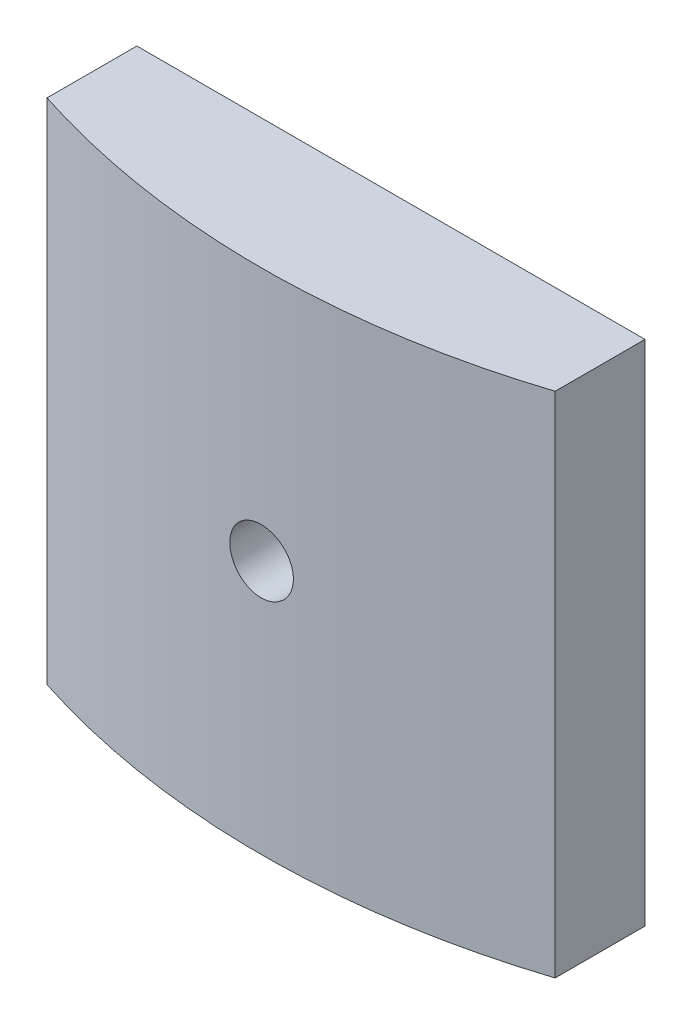
SolidWorks part; units mm, degrees
material "ABS"
ref_plane "Front Plane" through (0, 0, 0) normal (0, 0, 1) x (1, 0, 0)
ref_plane "Top Plane" through (0, 0, 0) normal (0, 1, 0) x (1, 0, 0)
ref_plane "Right Plane" through (0, 0, 0) normal (1, 0, 0) x (0, 0, -1)
sketch "Sketch2" plane through (0, 0, 0) normal (0, 1, 0) x (1, 0, 0)
  line L1 (-17.5, -27.3861) -> (17.5, -27.3861) construction
  line L2 (0, 0) -> (0, -60.5871) construction
  line L3 (0, -27.3861) -> (-10, -27.3861)
  line L4 (0, -27.3861) -> (10, -27.3861)
  line L7 (-10, -27.3861) -> (-10, -30.9233)
  line L8 (10, -27.3861) -> (10, -30.9233)
  circle A2 centre (0, 0) radius 32.5 construction
  arc A3 (-10, -30.9233) -> (10, -30.9233) centre (0, 0) ccw
  point P11 (0, -32.5)
  point P12 (0, -27.3861)
  dimension "D5" = 65
  dimension "D2" = 35
  dimension "D3" = 10
  dimension "D4" = 10
extrude "Boss-Extrude1" add sketch "Sketch2" along normal blind 20 contours L3 L7 A3 L8 L4
sketch "Sketch3" plane through (0, 0, 27.3861) normal (0, 0, -1) x (-1, 0, 0)
  line L0 (-10, 0) -> (10, 20) construction
  line L1 (-10, 20) -> (10, 0) construction
  circle A0 centre (0, 10) radius 1.25
  dimension "D1" = 2.5
extrude "Cut-Extrude1" cut sketch "Sketch3" against normal blind 20
